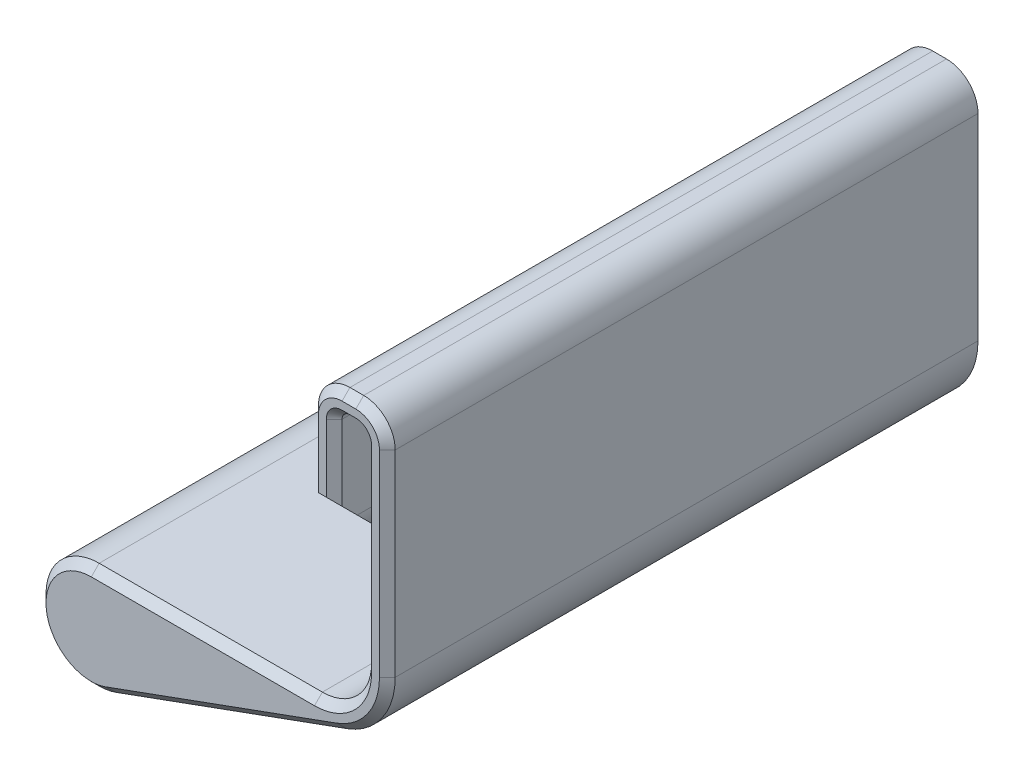
SolidWorks part; units mm, degrees
ref_plane "Front Plane" through (0, 0, 0) normal (0, 0, 1) x (1, 0, 0)
ref_plane "Top Plane" through (0, 0, 0) normal (0, 1, 0) x (1, 0, 0)
ref_plane "Right Plane" through (0, 0, 0) normal (1, 0, 0) x (0, 0, -1)
sketch "Sketch1" plane through (0, 0, 0) normal (0, 0, 1) x (1, 0, 0)
  line L0 (0, 0) -> (2.4, 0) construction
  line L1 (2.4, 0) -> (2.4, 9.2)
  line L2 (0, 0) -> (0, 9.2)
  line L3 (3.2, 10) -> (4.6, 10)
  line L4 (3.2, 12.4) -> (4.6, 12.4)
  line L5 (5.4, 9.2) -> (5.4, -10.8)
  line L6 (7.8, 9.2) -> (7.8, -10.8)
  line L7 (5.4, 9.2) -> (7.8, 9.2) construction
  line L8 (3.9, 10) -> (3.9, 12.4) construction
  line L9 (2.9309, -17.7537) -> (-20.5614, -26.3042)
  line L10 (0.4, -15.8) -> (-22.2715, -15.8)
  line L11 (-3.2971, -3.9598) -> (-0.4686, -1.1314)
  line L12 (-3.2971, -3.9598) -> (-1.6, -5.6569)
  line L13 (-1.6, -5.6569) -> (1.2284, -2.8284)
  arc A0 (2.4, 9.2) -> (3.2, 10) centre (3.2, 9.2) cw
  arc A1 (4.6, 10) -> (5.4, 9.2) centre (4.6, 9.2) cw
  arc A2 (0, 9.2) -> (3.2, 12.4) centre (3.2, 9.2) cw
  arc A3 (4.6, 12.4) -> (7.8, 9.2) centre (4.6, 9.2) cw
  arc A4 (5.4, -10.8) -> (0.4, -15.8) centre (0.4, -10.8) cw
  arc A5 (7.8, -10.8) -> (2.9309, -17.7537) centre (0.4, -10.8) cw
  arc A6 (-20.5614, -26.3042) -> (-22.2715, -26.6058) centre (-22.2715, -21.6058) cw
  arc A7 (-22.2715, -15.8) -> (-22.2715, -26.6058) centre (-22.2715, -21.2029) ccw
  arc A8 (0, 0) -> (-0.4686, -1.1314) centre (-1.6, 0) cw
  arc A9 (2.4, 0) -> (1.2284, -2.8284) centre (-1.6, 0) cw
  point P32 (-0.3873, -4.3668)
  dimension "D1" = 0.8
  dimension "D6" = 5
  dimension "D9" = 5
  dimension "D11" = 1.6
  dimension "D2" = 2.4
  dimension "D3" = 10
  dimension "D4" = 3
  dimension "D5" = 70
  dimension "D7" = 20
  dimension "D8" = 25
  dimension "D10" = 45
  dimension "D12" = 4
extrude "Boss-Extrude1" add sketch "Sketch1" along normal blind 60
chamfer "Chamfer2" distance 0.8 angle 45 20 edges at (0, 4.6, 60) (0.9373, 11.4627, 60) (3.9, 12.4, 60) (6.8627, 11.4627, 60) (7.8, -0.8, 60) (6.4617, -15.0445, 60) (-8.8152, -22.029, 60) (-21.4032, -26.5298, 60) (-27.6744, -21.2029, 60) (-10.9357, -15.8, 60) (3.9355, -14.3355, 60) (2.4, 4.6, 60) (5.4, -0.8, 60) (2.6343, 9.7657, 60) (5.1657, 9.7657, 60) (3.9, 10, 60) (-1.8828, -2.5456, 60) (-0.1218, -0.6123, 60) (-0.1858, -4.2426, 60) (2.0955, -1.5307, 60)
sketch "Sketch2" plane through (2.4, 0, 0) normal (1, 0, 0) x (0, 0, -1)
  line L0 (-60, 2.3431) -> (-52, -5.6569)
  line L1 (-52, -5.6569) -> (-60, -5.6569)
  line L2 (-60, -5.6569) -> (-60, 2.3431)
  line L3 (-59.2, -5.6569) -> (0, -5.6569) construction
  line L4 (-60, 0) -> (-60, 9.2) construction
  line L5 (0, 2.3431) -> (-8, -5.6569)
  line L6 (-8, -5.6569) -> (0, -5.6569)
  line L7 (0, -5.6569) -> (0, 2.3431)
  dimension "D1" = 8
extrude "Cut-Extrude1" cut sketch "Sketch2" against normal through all
fillet "Fillet2" radius 0.8 2 edges at (-1.6, -5.6569, 30) (-3.2971, -3.9598, 30)
